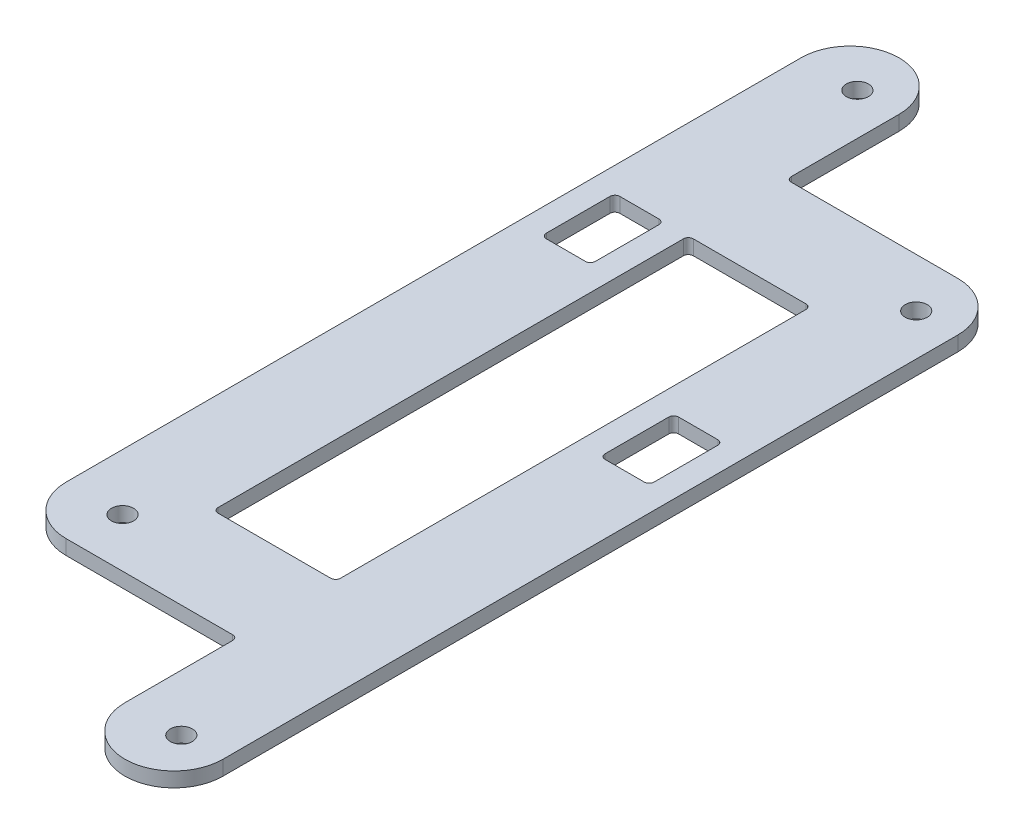
SolidWorks part; units mm, degrees
material "ABS"
ref_plane "Front Plane" through (0, 0, 0) normal (0, 0, 1) x (1, 0, 0)
ref_plane "Top Plane" through (0, 0, 0) normal (0, 1, 0) x (1, 0, 0)
ref_plane "Right Plane" through (0, 0, 0) normal (1, 0, 0) x (0, 0, -1)
sketch "Sketch1" plane through (0, 0, 0) normal (0, 1, 0) x (1, 0, 0)
  line L0 (-45, 0) -> (0, 0) construction
  line L1 (0, 117) -> (0, -33) construction
  line L6 (-45, 0) -> (-45, 150) construction
  line L7 (-45, 117) -> (0, 117) construction
  line L8 (-35, 10) -> (-10, 10)
  line L9 (-35, 10) -> (-35, 107)
  line L10 (-35, 107) -> (-10, 107)
  line L11 (-10, 107) -> (-10, 10)
  line L12 (-45, -10) -> (-10, -10)
  line L13 (-55, 0) -> (-55, 150)
  line L14 (-35, 127) -> (0, 127)
  line L15 (10, 117) -> (10, -33)
  line L16 (-45, 107) -> (-10, 107) construction
  line L17 (-45, 127) -> (10, 127) construction
  line L18 (-35, 127) -> (-35, 150)
  line L19 (-35, 10) -> (-35, 150) construction
  line L20 (-10, -10) -> (-10, -33)
  line L21 (-10, 107) -> (-10, -33) construction
  line L22 (-55, -10) -> (0, -10) construction
  line L23 (-35, 10) -> (0, 10) construction
  line L24 (10, 127) -> (10, -33) construction
  line L25 (-55, -10) -> (-55, 150) construction
  line L26 (-45, 150) -> (-43.5, 150) construction
  line L27 (0, 117) -> (1.5, 117) construction
  line L28 (0, -33) -> (1.5, -33) construction
  line L29 (-45, 0) -> (-43.5, 0) construction
  arc A3 (-35, 150) -> (-55, 150) centre (-45, 150) ccw
  arc A5 (-10, -33) -> (10, -33) centre (0, -33) ccw
  arc A6 (0, 127) -> (10, 117) centre (0, 117) cw
  arc A7 (-45, -10) -> (-55, 0) centre (-45, 0) cw
  dimension "D7" = 10
  dimension "D1" = 33
  dimension "D2" = 45
  dimension "D3" = 150
  dimension "D4" = 33
  dimension "D8" = 1.5
  dimension "D9" = 1.5
  dimension "D10" = 1.5
  dimension "D5" = 10
  dimension "D6" = 10
extrude "Boss-Extrude1" add sketch "Sketch1" along normal blind 3
sketch "Sketch4" plane through (0, 3, 0) normal (0, 1, 0) x (1, 0, 0)
  line L1 (-40, 92) -> (-50, 92)
  line L2 (-40, 92) -> (-40, 107)
  line L3 (-40, 107) -> (-50, 107)
  line L4 (-50, 92) -> (-50, 107)
  line L5 (-40, 92) -> (-50, 107) construction
  line L6 (-40, 107) -> (-50, 92) construction
  line L8 (5, 59) -> (-5, 59)
  line L9 (5, 59) -> (5, 74)
  line L10 (5, 74) -> (-5, 74)
  line L11 (-5, 59) -> (-5, 74)
  line L12 (5, 59) -> (-5, 74) construction
  line L13 (5, 74) -> (-5, 59) construction
  line L18 (0, 117) -> (0, -33) construction
  line L19 (-45, 0) -> (-45, 150) construction
  point P0 (-45, 99.5)
  point P5 (-48.1852, 99.6006)
  point P6 (0, 66.5)
  point P7 (0, 66.5)
  point P13 (-2.3039, 66.4466)
  point P17 (-35, 98.5151)
  point P18 (-45, 99.5)
  dimension "D1" = 10
  dimension "D2" = 15
  dimension "D5" = 50.5
  dimension "D6" = 50.5
extrude "Cut-Extrude1" cut sketch "Sketch4" against normal through all
fillet "Fillet2" radius 1 14 edges at (-35, 1.5, -127) (-10, 1.5, 10) (-10, 1.5, -10) (-10, 1.5, -107) (-35, 1.5, -107) (-35, 1.5, -10) (5, 1.5, -74) (5, 1.5, -59) (-5, 1.5, -74) (-5, 1.5, -59) (-40, 1.5, -107) (-40, 1.5, -92) (-50, 1.5, -107) (-50, 1.5, -92)
hole_wizard "M4 Clearance Hole1" positions "Sketch2" profile "Sketch3" hole size "M4" standard "ANSI Metric" end condition through all
sketch "Sketch2" plane through (0, 3, 0) normal (0, 1, 0) x (1, 0, 0)
  point P24 (-43.5, 150)
  point P27 (1.5, 117)
  point P30 (-43.5, 0)
  point P43 (1.5, -33)
sketch "Sketch3" plane through (-43.5, 3, -150) normal (1, 0, 0) x (0, 0, 1)
  line L0 (0, 0) -> (0, 3)
  line L1 (0, 3) -> (2.25, 3)
  line L2 (2.25, 3) -> (2.25, 0)
  line L5 (2.25, 0) -> (0, 0)
  line L11 (0, -6.35) -> (0, 107.95) construction
  dimension "Thru Hole Dia." = 4.5
  dimension "Thru Hole Depth" = 3
